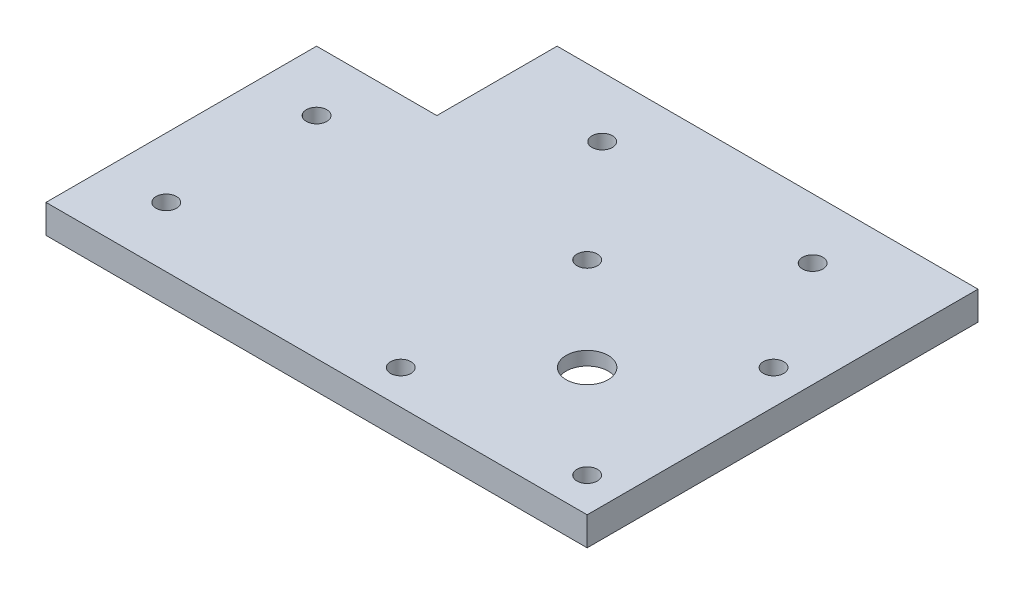
SolidWorks part; units mm, degrees
material "6061 Alloy"
ref_plane "Front Plane" through (0, 0, 0) normal (0, 0, 1) x (1, 0, 0)
ref_plane "Top Plane" through (0, 0, 0) normal (0, 1, 0) x (1, 0, 0)
ref_plane "Right Plane" through (0, 0, 0) normal (1, 0, 0) x (0, 0, -1)
sketch "Sketch1" plane through (0, 0, 0) normal (0, 1, 0) x (1, 0, 0)
  line L0 (0, 0) -> (0, 45)
  line L1 (0, 45) -> (20, 45)
  line L12 (90, 65) -> (20, 65)
  line L13 (90, 0) -> (90, 65)
  line L14 (90, 0) -> (0, 0)
  line L16 (20, 65) -> (20, 45)
  dimension "D1" = 65
  dimension "D2" = 45
  dimension "D3" = 70
extrude "Boss-Extrude1" add sketch "Sketch1" along normal blind 4.7625
sketch "Sketch3" plane through (0, 0, 0) normal (0, -1, 0) x (1, 0, 0)
  line L0 (0, -45) -> (0, 0) construction
  line L3 (10, 0) -> (10, -55) construction
  line L4 (10, -55) -> (90, -55) construction
  line L5 (0, -22.5) -> (10, -22.5) construction
  line L6 (55, -55) -> (55, -65) construction
  line L7 (0, 0) -> (90, 0) construction
  line L8 (90, -65) -> (20, -65) construction
  line L9 (90, 0) -> (90, -65) construction
  point P12 (10, -10)
  point P22 (53.291, -5.709)
  point P23 (10, -35)
  point P25 (84.291, -5.709)
  point P27 (72.5, -55)
  point P28 (68.791, -21.209)
  point P29 (84.291, -36.709)
  point P30 (53.291, -36.709)
  point P31 (37.5, -55)
  dimension "D1" = 10
  dimension "D2" = 22.5
  dimension "D3" = 10
  dimension "D4" = 10
  dimension "D5" = 35
  dimension "D6" = 17.5
hole_wizard "Ø7.0 (7) Diameter Hole1" positions "Sketch8" profile "Sketch9" hole size "Ø7.0" standard "ANSI Metric" end condition through all
sketch "Sketch8" plane through (0, 0, 0) normal (0, -1, 0) x (-1, 0, 0)
  point P0 (-68.791, 21.209)
sketch "Sketch9" plane through (68.791, 0, -21.209) normal (1, 0, 0) x (0, 0, -1)
  line L0 (0, 0) -> (0, 4.7625)
  line L1 (0, 4.7625) -> (3.5, 4.7625)
  line L2 (3.5, 4.7625) -> (3.5, 0)
  line L5 (3.5, 0) -> (0, 0)
  line L11 (0, -6.35) -> (0, 107.95) construction
  dimension "Thru Hole Dia." = 7
  dimension "Thru Hole Depth" = 4.7625
sketch "Sketch12" plane through (0, 0, 0) normal (0, -1, 0) x (1, 0, 0)
  circle A0 centre (68.791, -21.209) radius 11.5
extrude "Cut-Extrude1" cut sketch "Sketch12" against normal blind 2.5
sketch "Sketch14" plane through (0, 4.7625, 0) normal (0, 1, 0) x (1, 0, 0)
  line L20 (37.291, 11.209) -> (30.291, 31.209) construction
  line L21 (37.291, 31.209) -> (30.291, 11.209) construction
  line L22 (47.582, 21.209) -> (20, 21.209) construction
  line L23 (20, 45) -> (20, 0) construction
  line L24 (30.291, 31.209) -> (30.291, 11.209)
  line L25 (37.291, 11.209) -> (30.291, 11.209)
  line L26 (37.291, 31.209) -> (37.291, 11.209)
  line L27 (37.291, 31.209) -> (30.291, 31.209)
  line L28 (90, 37.097) -> (90, 5.321)
  line L29 (84.679, 0) -> (52.903, 0)
  line L30 (47.582, 5.321) -> (47.582, 37.097)
  line L31 (52.903, 42.418) -> (84.679, 42.418)
  circle A16 centre (37.291, 11.209) radius 6.1 construction
  circle A17 centre (30.291, 31.209) radius 6.1 construction
  circle A18 centre (68.791, 21.209) radius 6.1 construction
  circle A19 centre (37.291, 11.209) radius 7.5
  circle A20 centre (30.291, 31.209) radius 7.5
  arc A21 (90, 5.321) -> (84.679, 0) centre (68.791, 21.209) cw
  arc A22 (52.903, 0) -> (47.582, 5.321) centre (68.791, 21.209) cw
  arc A23 (47.582, 37.097) -> (52.903, 42.418) centre (68.791, 21.209) cw
  arc A24 (84.679, 42.418) -> (90, 37.097) centre (68.791, 21.209) cw
  circle A25 centre (68.791, 21.209) radius 7.5
  point P87 (22.791, 31.209)
  point P88 (33.791, 21.209)
hole_wizard "M3 Clearance Hole1" positions "Sketch17" profile "Sketch18" hole size "M3" standard "ANSI Metric" end condition through all
sketch "Sketch17" plane through (0, 0, 0) normal (0, -1, 0) x (-1, 0, 0)
  point P0 (-10, 10)
  point P3 (-10, 35)
  point P6 (-37.5, 55)
  point P9 (-72.5, 55)
  point P12 (-84.291, 36.709)
  point P15 (-84.291, 5.709)
  point P18 (-53.291, 5.709)
  point P21 (-53.291, 36.709)
sketch "Sketch18" plane through (10, 0, -10) normal (1, 0, 0) x (0, 0, -1)
  line L0 (0, 0) -> (0, 4.7625)
  line L1 (0, 4.7625) -> (1.7, 4.7625)
  line L2 (1.7, 4.7625) -> (1.7, 0)
  line L5 (1.7, 0) -> (0, 0)
  line L11 (0, -6.35) -> (0, 107.95) construction
  dimension "Thru Hole Dia." = 3.4
  dimension "Thru Hole Depth" = 4.7625
